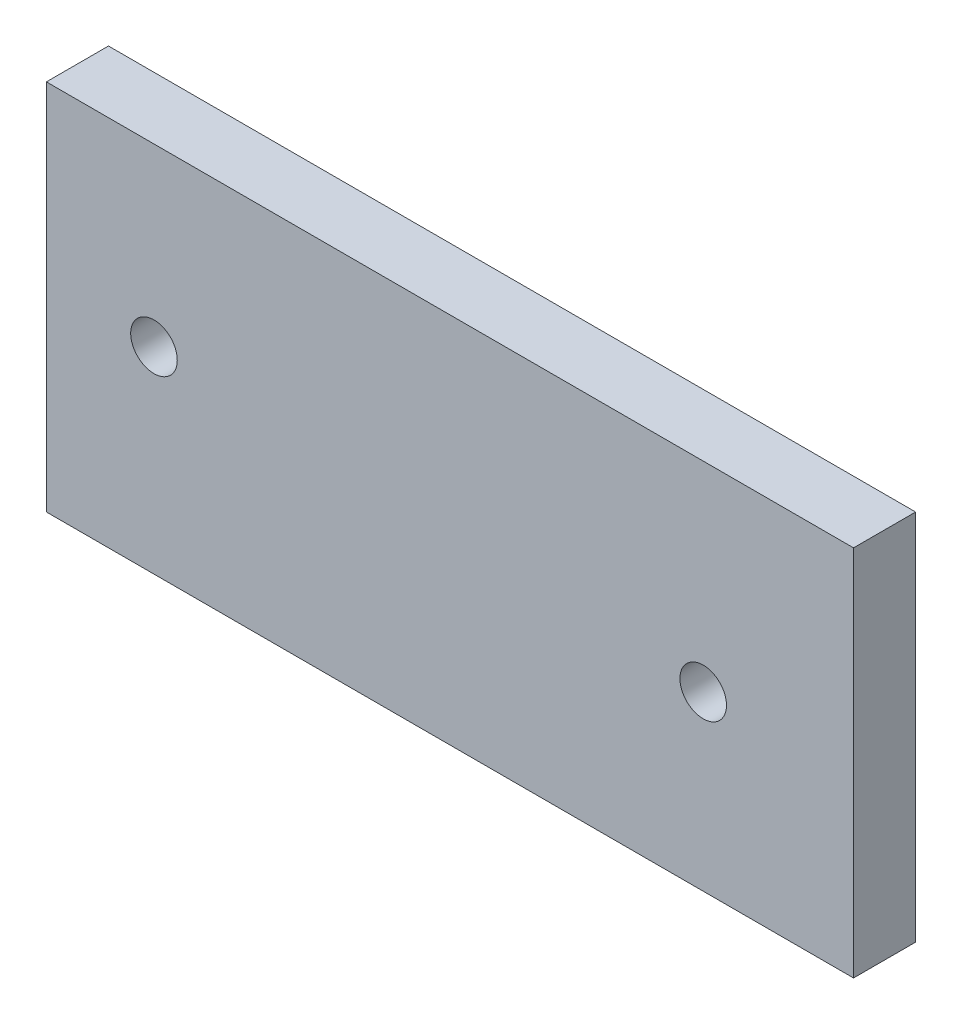
SolidWorks part; units mm, degrees
ref_plane "Front Plane" through (0, 0, 0) normal (0, 0, 1) x (1, 0, 0)
ref_plane "Top Plane" through (0, 0, 0) normal (0, 1, 0) x (1, 0, 0)
ref_plane "Right Plane" through (0, 0, 0) normal (1, 0, 0) x (0, 0, -1)
sketch "Sketch1" plane through (0, 0, 0) normal (0, 0, 1) x (1, 0, 0)
  line L1 (0, 0) -> (260, 0)
  line L2 (0, 0) -> (0, 120)
  line L3 (0, 120) -> (260, 120)
  line L4 (260, 0) -> (260, 120)
  dimension "D1" = 260
  dimension "D2" = 120
extrude "Boss-Extrude1" add sketch "Sketch1" along normal blind 20
sketch "Sketch2" plane through (0, 0, 20) normal (0, 0, 1) x (1, 0, 0)
  circle A0 centre (34.659, 63.4233) radius 7.5
  circle A1 centre (211.5778, 55.5935) radius 7.5
  point P4 (0, 0)
  point P5 (214.7955, 63.4233)
  point P6 (214.4457, 74.1615)
  point P7 (216.1943, 48.9816)
  point P8 (218.283, 55.508)
  point P9 (0, 0)
  point P10 (212.6226, 59.031)
  point P11 (0, 0)
  point P12 (212.1484, 63.4233)
  point P13 (212.1484, 63.4233)
  point P14 (208.592, 59.7422)
  point P15 (215.0002, 60.4236)
  point P16 (207.3123, 59.552)
  point P17 (209.6872, 56.854)
  point P18 (212.0611, 60.4711)
  point P19 (0, 0)
  point P20 (211.5778, 55.5935)
extrude "Cut-Extrude2" cut sketch "Sketch2" against normal blind 30
